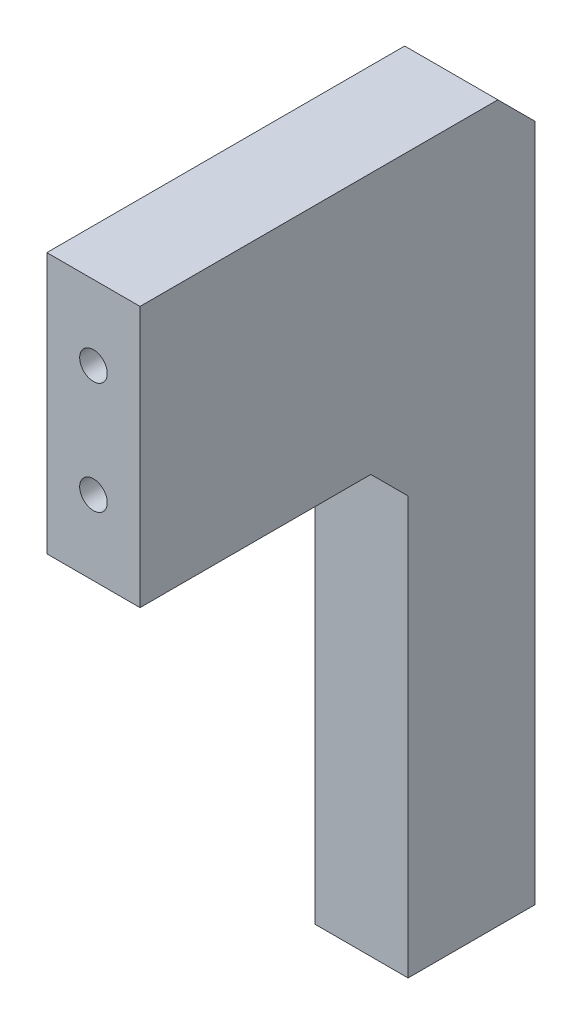
SolidWorks part; units mm, degrees
ref_plane "Front Plane" through (0, 0, 0) normal (0, 0, 1) x (1, 0, 0)
ref_plane "Top Plane" through (0, 0, 0) normal (0, 1, 0) x (1, 0, 0)
ref_plane "Right Plane" through (0, 0, 0) normal (1, 0, 0) x (0, 0, -1)
sketch "Sketch1" plane through (0, 0, 0) normal (1, 0, 0) x (0, 0, -1)
  line L0 (0, 0) -> (-17.045, 0)
  line L5 (-17.045, 0) -> (-17.045, 61)
  line L6 (-17.045, 61) -> (-53, 61)
  line L7 (-53, 61) -> (-53, 96)
  line L8 (-53, 96) -> (0, 96)
  line L9 (0, 96) -> (0, 0)
  point P5 (-8.5225, 0)
  dimension "D1" = 17.045
  dimension "D2" = 53
  dimension "D3" = 61
  dimension "D4" = 96
extrude "Boss-Extrude1" add sketch "Sketch1" along normal mid plane 12.5
chamfer "Chamfer1" distance 5 angle 45 2 edges at (0, 61, 17.045) (0, 96, 0)
hole_wizard "Ø3.7 (3.7) Diameter Hole1" positions "Sketch2" profile "Sketch3" hole size "Ø3.7" standard "ANSI Metric"
sketch "Sketch2" plane through (0, 0, 53) normal (0, 0, 1) x (1, 0, 0)
  line L0 (0, 86) -> (0, 71) construction
  line L2 (0, 78.5) -> (6.25, 78.5) construction
  line L3 (6.25, 96) -> (6.25, 61) construction
  line L5 (0, 96) -> (0, 86) construction
  line L6 (6.25, 96) -> (-6.25, 96) construction
  point P0 (0, 86)
  point P2 (0, 71)
  dimension "D1" = 15
sketch "Sketch3" plane through (0, 86, 53) normal (1, 0, 0) x (0, -1, 0)
  line L0 (0, 0) -> (0, 13.1116)
  line L1 (0, 13.1116) -> (1.85, 12)
  line L2 (1.85, 12) -> (1.85, 0)
  line L5 (1.85, 0) -> (0, 0)
  line L10 (0, 13.1116) -> (-1.85, 12) construction
  line L11 (0, -6.35) -> (0, 107.95) construction
  dimension "Hole Dia." = 3.7
  dimension "Hole Depth" = 12
  dimension "Drill Angle" = 118
hole_wizard "Ø3.7 (3.7) Diameter Hole2" positions "Sketch4" profile "Sketch5" hole size "Ø3.7" standard "ANSI Metric"
sketch "Sketch4" plane through (0, 0, 0) normal (0, -1, 0) x (-1, 0, 0)
  line L3 (0, -10.22) -> (0, 0) construction
  point P0 (0, -10.22)
  dimension "D1" = 10.22
sketch "Sketch5" plane through (0, 0, 10.22) normal (1, 0, 0) x (0, 0, -1)
  line L0 (0, 0) -> (0, 21.1116)
  line L1 (0, 21.1116) -> (1.85, 20)
  line L2 (1.85, 20) -> (1.85, 0)
  line L5 (1.85, 0) -> (0, 0)
  line L10 (0, 21.1116) -> (-1.85, 20) construction
  line L11 (0, -6.35) -> (0, 107.95) construction
  dimension "Hole Dia." = 3.7
  dimension "Hole Depth" = 20
  dimension "Drill Angle" = 118
